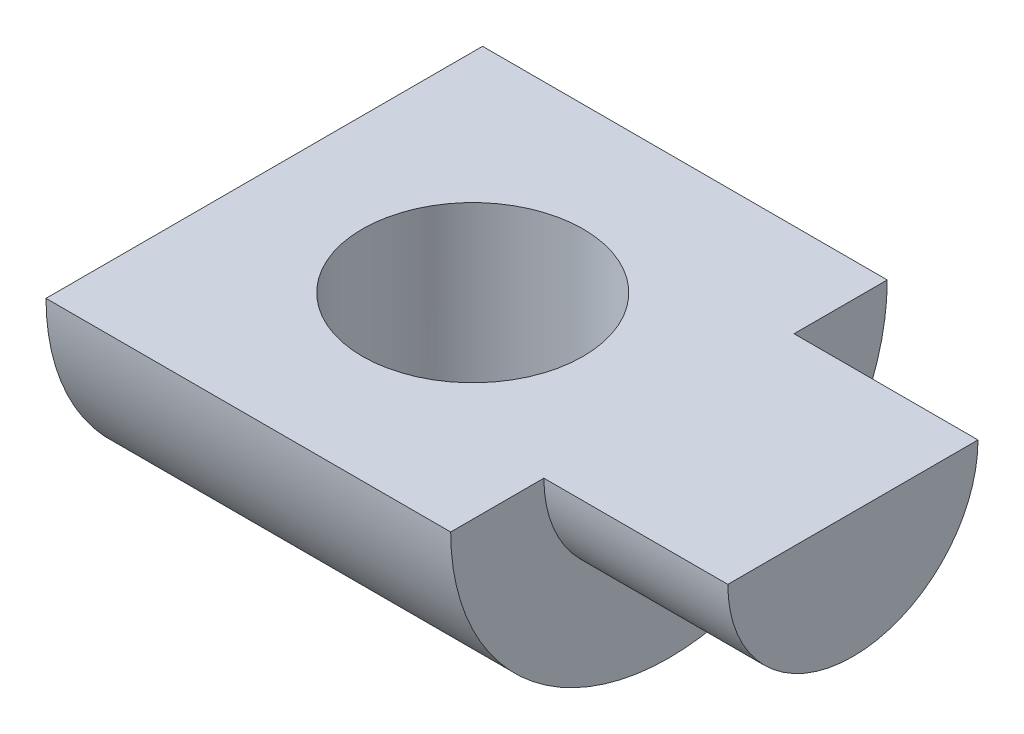
SolidWorks part; units mm, degrees
ref_plane "Piano frontale" through (0, 0, 0) normal (0, 0, 1) x (1, 0, 0)
ref_plane "Piano superiore" through (0, 0, 0) normal (0, 1, 0) x (1, 0, 0)
ref_plane "Piano destro" through (0, 0, 0) normal (1, 0, 0) x (0, 0, -1)
sketch "Schizzo1" plane through (0, 0, 0) normal (0, 1, 0) x (1, 0, 0)
  line L1 (-120, 89) -> (45, 89)
  line L2 (-120, 89) -> (-120, -89)
  line L3 (-120, -89) -> (45, -89)
  line L4 (45, 89) -> (45, -89)
  dimension "D1" = 165
  dimension "D2" = 178
  dimension "D3" = 120
  dimension "D4" = 89
extrude "Estrusione-Estrusione3" add sketch "Schizzo1" against normal blind 89 contours L1 L4 L3 L2
sketch "Schizzo3" plane through (45, 0, 0) normal (1, 0, 0) x (0, 0, -1)
  line L3 (89, 0) -> (-89, 0) construction
  line L4 (-89, 0) -> (-89, -89)
  line L5 (-89, -89) -> (89, -89)
  line L6 (89, -89) -> (89, 0)
  circle A0 centre (0, 0) radius 89
  point P12 (0, 0)
  line M3 (-89, 0) -> (-89, -89)
  line M4 (-89, -89) -> (89, -89)
  line M5 (89, -89) -> (89, 0)
  dimension "D1" = 178
extrude "Taglio-Estrusione1" cut sketch "Schizzo3" against normal through all contours A0 L5 M5 | A0 M3 M4
sketch "Schizzo4" plane through (45, 0, 0) normal (1, 0, 0) x (0, 0, -1)
  line L0 (89, 0) -> (-89, 0) construction
  line L1 (-51, 0) -> (51, 0)
  arc A0 (51, 0) -> (-51, 0) centre (0, 0) cw
  dimension "D1" = 102
extrude "Estrusione-Estrusione5" add sketch "Schizzo4" along normal blind 75
sketch "Schizzo6" plane through (0, 0, 0) normal (0, 1, 0) x (1, 0, 0)
  line L0 (-120, 89) -> (-120, -89) construction
  line L1 (-120, 89) -> (45, 89) construction
  circle A0 centre (-35, 0) radius 45
  dimension "D3" = 90
  dimension "D1" = 85
  dimension "D2" = 89
extrude "Taglio-Estrusione2" cut sketch "Schizzo6" against normal through all
